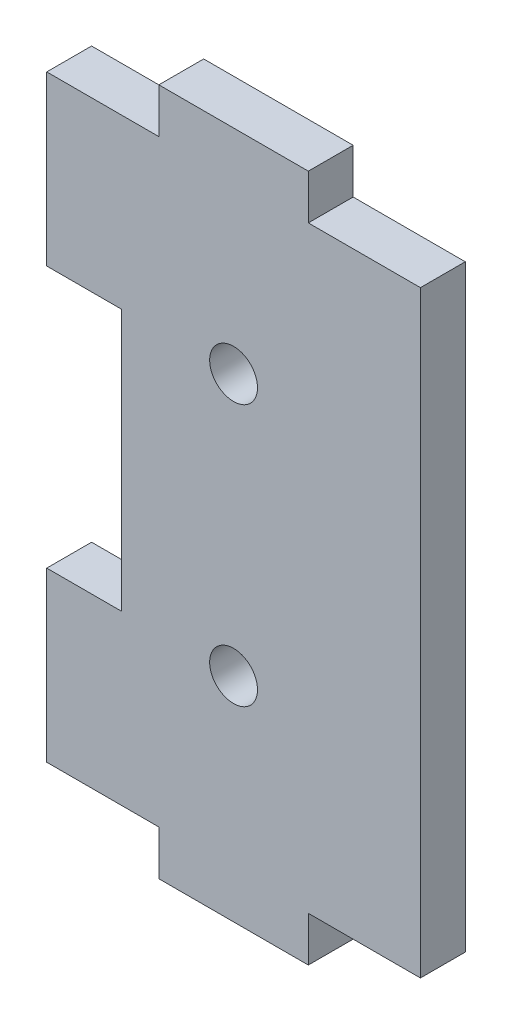
SolidWorks part; units mm, degrees
ref_plane "Front Plane" through (0, 0, 0) normal (0, 0, 1) x (1, 0, 0)
ref_plane "Top Plane" through (0, 0, 0) normal (0, 1, 0) x (1, 0, 0)
ref_plane "Right Plane" through (0, 0, 0) normal (1, 0, 0) x (0, 0, -1)
sketch "Sketch1" plane through (0, 0, 0) normal (0, 0, 1) x (1, 0, 0)
  line L0 (-5, 20) -> (-5, 23)
  line L1 (-5, -23) -> (5, -23)
  line L2 (-5, -23) -> (-5, -20)
  line L3 (-5, 23) -> (5, 23)
  line L4 (5, -23) -> (5, -20)
  line L5 (-5, -23) -> (5, 23) construction
  line L6 (-5, 23) -> (5, -23) construction
  line L7 (-12.5, 20) -> (-5, 20)
  line L11 (-12.5, 20) -> (-12.5, 8.75)
  line L12 (12.5, 20) -> (12.5, -20)
  line L13 (5, 20) -> (5, 23)
  line L14 (-5, 0) -> (5, 0) construction
  line L15 (-12.5, 8.75) -> (-7.5, 8.75)
  line L16 (-7.5, 8.75) -> (-7.5, -8.75)
  line L20 (-12.5, -20) -> (-5, -20)
  line L22 (5, 20) -> (12.5, 20)
  line L23 (5, -20) -> (12.5, -20)
  line L24 (-7.5, -8.75) -> (-12.5, -8.75)
  line L26 (-12.5, -8.75) -> (-12.5, -20)
  circle A0 centre (0, 8.75) radius 1.6
  circle A2 centre (0, -8.75) radius 1.6
  point P0 (0, 0)
  dimension "D3" = 3.2
  dimension "D10" = 3.2
  dimension "D1" = 46
  dimension "D2" = 10
  dimension "D4" = 25
  dimension "D5" = 12.5
  dimension "D6" = 8.75
  dimension "D7" = 3
  dimension "D8" = 17.5
  dimension "D9" = 5
  dimension "D11" = 17.5
extrude "Boss-Extrude1" add sketch "Sketch1" along normal blind 3
